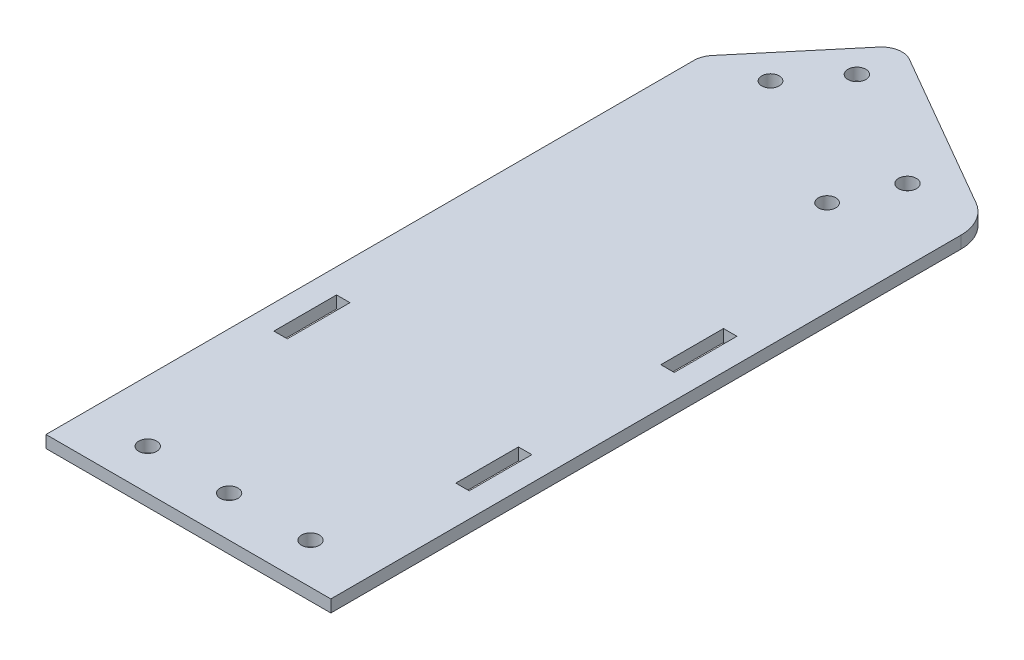
SolidWorks part; units mm, degrees
material "Thornel Mat VMA"
ref_plane "前视基准面" through (0, 0, 0) normal (0, 0, 1) x (1, 0, 0)
ref_plane "上视基准面" through (0, 0, 0) normal (0, 1, 0) x (1, 0, 0)
ref_plane "右视基准面" through (0, 0, 0) normal (1, 0, 0) x (0, 0, -1)
other "Configuration Table"
sketch "草图1" plane through (0, 0, 0) normal (0, 1, 0) x (1, 0, 0)
  line L0 (35, 80.34) -> (-35, 120.7545)
  line L1 (-35, 80.34) -> (35, 80.34)
  line L2 (-35, 80.34) -> (-35, -80.34)
  line L3 (-35, -80.34) -> (35, -80.34)
  line L4 (35, 80.34) -> (35, -80.34)
  line L5 (-35, 80.34) -> (35, -80.34) construction
  line L6 (-35, -80.34) -> (35, 80.34) construction
  line L7 (-35, 120.7545) -> (-35, 80.34)
  point P0 (0, 0)
  dimension "D1" = 70
  dimension "D2" = 160.68
  dimension "D3" = 30
extrude "凸台-拉伸1" add sketch "草图1" along normal mid plane 3 contours L4 L1 L2 L3 | L0 L7 L1
sketch "草图2" plane through (0, 1.5, 0) normal (0, 1, 0) x (1, 0, 0)
  line L0 (-7, 104.5887) -> (-12, 95.9285) construction
  line L1 (35, 80.34) -> (-35, 120.7545) construction
  line L2 (-12, 95.9285) -> (17.4449, 78.9285) construction
  circle A1 centre (-12, 95.9285) radius 2.2
  circle A2 centre (17.4449, 78.9285) radius 2.2
  dimension "D4" = 4.4
  dimension "D3" = 12
  dimension "D1" = 10
  dimension "D2" = 34
extrude "切除-拉伸1" cut sketch "草图2" against normal through all both and the other way through all
fillet "圆角2" radius 10 1 edges at (35, 0, -80.34)
sketch "草图3" plane through (0, 1.5, 0) normal (0, 1, 0) x (1, 0, 0)
  line L0 (-35, -80.34) -> (35, -80.34) construction
  line L1 (-20, -70.34) -> (20, -70.34) construction
  line L2 (-20, -70.34) -> (-20, -90.34) construction
  line L3 (-20, -90.34) -> (20, -90.34) construction
  line L4 (20, -70.34) -> (20, -90.34) construction
  line L5 (-20, -70.34) -> (20, -90.34) construction
  line L6 (-20, -90.34) -> (20, -70.34) construction
  circle A0 centre (0, -70.34) radius 2.2
  circle A1 centre (-20, -70.34) radius 2.2
  circle A2 centre (20, -70.34) radius 2.2
  point P0 (0, -80.34)
  dimension "D3" = 4.4
  dimension "D1" = 20
  dimension "D2" = 40
extrude "切除-拉伸2" cut sketch "草图3" against normal through all both and the other way through all
chamfer "倒角2" distance 40 angle 40 1 edges at (-35, 0, -120.7545)
fillet "圆角3" radius 5 2 edges at (-35, 0, -80.7545) (-12.3897, 0, -107.7004)
sketch "草图4" plane through (0, 1.5, 0) normal (0, 1, 0) x (1, 0, 0)
  line L0 (-35, 78.9347) -> (-35, -80.34) construction
  line L1 (-29, -14.94) -> (-25.7, -14.94)
  line L2 (-29, -14.94) -> (-29, -30.34)
  line L3 (-29, -30.34) -> (-25.7, -30.34)
  line L4 (-25.7, -14.94) -> (-25.7, -30.34)
  line L5 (-35, -80.34) -> (35, -80.34) construction
  line L6 (35, 74.5665) -> (35, -80.34) construction
  line L7 (25.7, -24.94) -> (29, -24.94)
  line L8 (25.7, -24.94) -> (25.7, -40.34)
  line L9 (25.7, -40.34) -> (29, -40.34)
  line L10 (29, -24.94) -> (29, -40.34)
  line L11 (25.7, 25.46) -> (25.7, 10.06)
  line L12 (25.7, 25.46) -> (29, 25.46)
  line L13 (29, 25.46) -> (29, 10.06)
  line L14 (25.7, 10.06) -> (29, 10.06)
  dimension "D1" = 3.3
  dimension "D2" = 15.4
  dimension "D3" = 6
  dimension "D4" = 50
  dimension "D5" = 3.3
  dimension "D6" = 15.4
  dimension "D7" = 6
  dimension "D8" = 40
  dimension "D10" = 35
  dimension "D9" = 2
extrude "切除-拉伸3" cut sketch "草图4" against normal through all both and the other way through all
sketch "草图5" plane through (0, 1.5, 0) normal (0, 1, 0) x (1, 0, 0)
  circle A0 centre (-21.2321, 83.9381) radius 2.15
  circle A1 centre (11.6769, 64.9381) radius 2.15
  dimension "D1" = 4.3
  dimension "D2" = 4.3
extrude "切除-拉伸4" cut sketch "草图5" against normal blind 10
